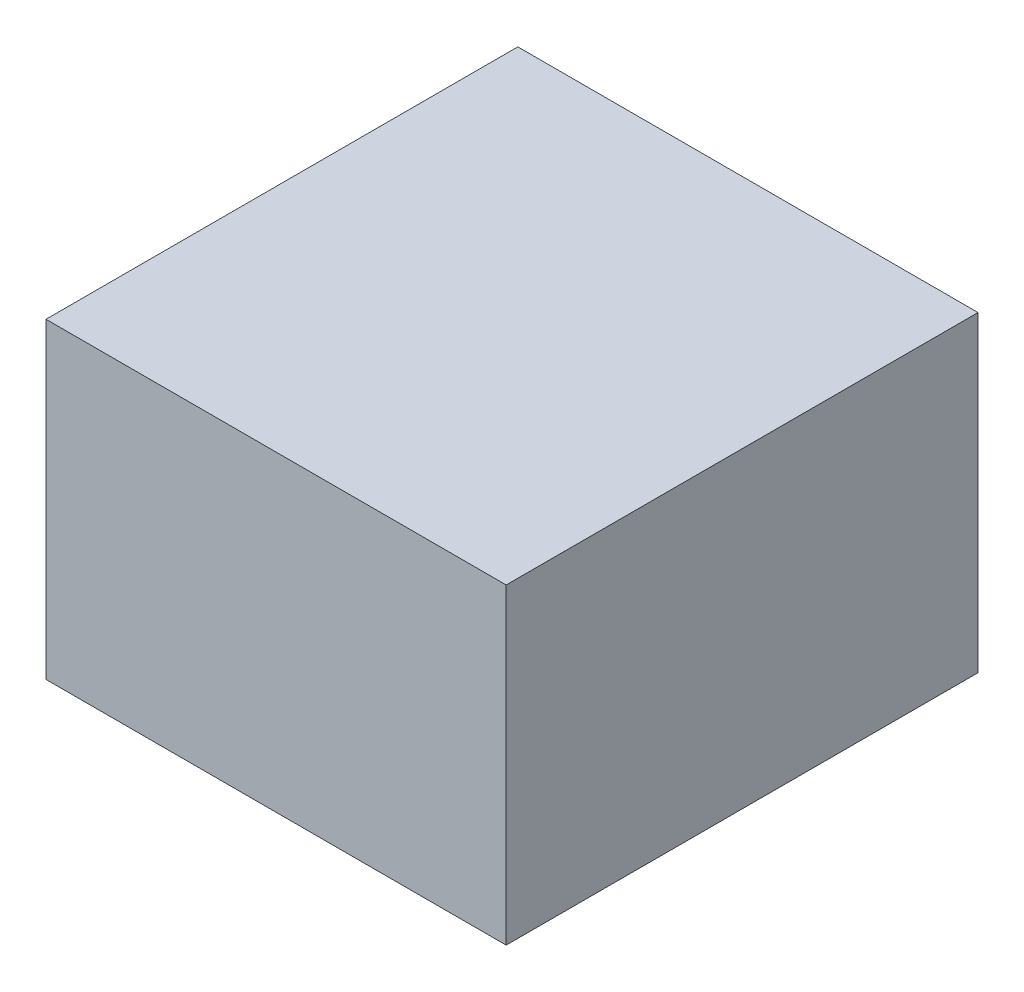
SolidWorks part; units mm, degrees
ref_plane "Front Plane" through (0, 0, 0) normal (0, 0, 1) x (1, 0, 0)
ref_plane "Top Plane" through (0, 0, 0) normal (0, 1, 0) x (1, 0, 0)
ref_plane "Right Plane" through (0, 0, 0) normal (1, 0, 0) x (0, 0, -1)
sketch "Sketch1" plane through (0, 0, 0) normal (0, 1, 0) x (1, 0, 0)
  line L0 (-78.6892, 80.6778) -> (78.6892, -80.6778) construction
  line L1 (-78.6892, 80.6778) -> (78.6892, 80.6778)
  line L2 (-78.6892, 80.6778) -> (-78.6892, -80.6778)
  line L3 (-78.6892, -80.6778) -> (78.6892, -80.6778)
  line L4 (78.6892, 80.6778) -> (78.6892, -80.6778)
extrude "Boss-Extrude1" add sketch "Sketch1" along normal mid plane 106.68
sketch "Sketch2" plane through (0, 0, 80.6778) normal (0, 0, 1) x (1, 0, 0)
  line L0 (-76.2, 50.8) -> (76.2, -50.8) construction
  line L1 (-63.5, 50.8) -> (63.5, 50.8)
  line L2 (-76.2, 38.1) -> (-76.2, -38.1)
  line L3 (-63.5, -50.8) -> (63.5, -50.8)
  line L4 (76.2, 38.1) -> (76.2, -38.1)
  arc A0 (-76.2, -38.1) -> (-63.5, -50.8) centre (-63.5, -38.1) ccw
  arc A1 (63.5, -50.8) -> (76.2, -38.1) centre (63.5, -38.1) ccw
  arc A2 (63.5, 50.8) -> (76.2, 38.1) centre (63.5, 38.1) cw
  arc A3 (-63.5, 50.8) -> (-76.2, 38.1) centre (-63.5, 38.1) ccw
  dimension "D1" = 12.7
  dimension "D2" = 152.4
  dimension "D3" = 101.6
sketch "Sketch3" plane through (0, 0, -80.6778) normal (0, 0, -1) x (-1, 0, 0)
  circle A0 centre (0, 0) radius 23.8125
  dimension "D1" = 47.625
